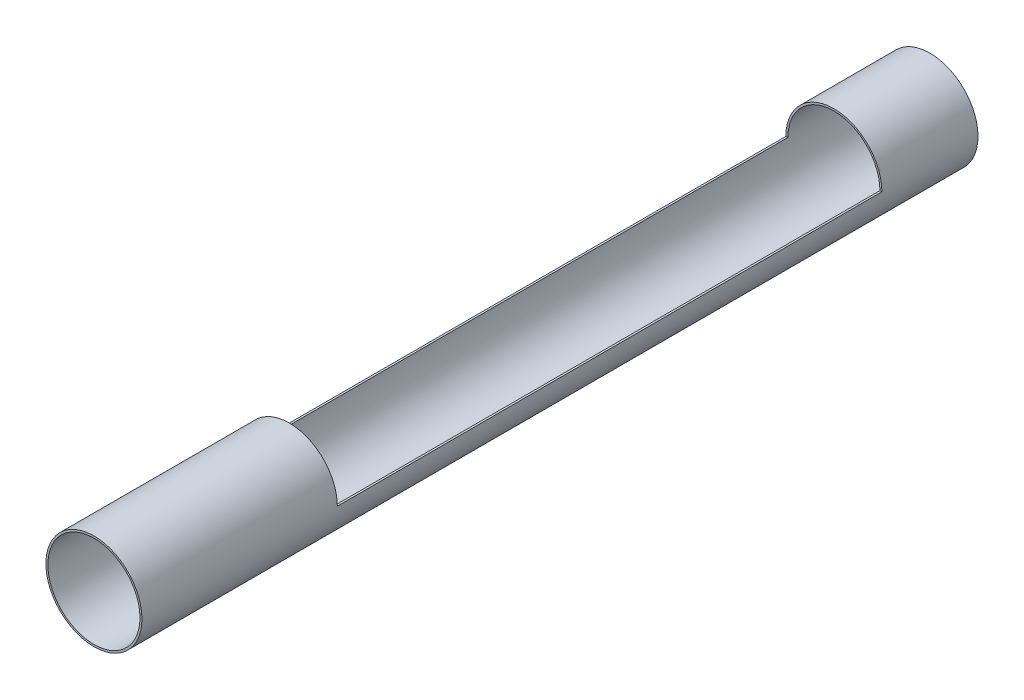
SolidWorks part; units mm, degrees
ref_plane "Front Plane" through (0, 0, 0) normal (0, 0, 1) x (1, 0, 0)
ref_plane "Top Plane" through (0, 0, 0) normal (0, 1, 0) x (1, 0, 0)
ref_plane "Right Plane" through (0, 0, 0) normal (1, 0, 0) x (0, 0, -1)
sketch "Sketch1" plane through (0, 0, 0) normal (0, 0, 1) x (1, 0, 0)
  circle A0 centre (0, 0) radius 36.5125
  circle A1 centre (0, 0) radius 38.0746
  dimension "D1" = 73.025
  dimension "D2" = 76.1492
extrude "Boss-Extrude1" add sketch "Sketch1" along normal blind 76.2
sketch "Sketch2" plane through (0, 0, 76.2) normal (0, 0, 1) x (1, 0, 0)
  line L0 (-38.0746, 0) -> (-36.5125, 0)
  line L1 (38.0746, 0) -> (36.5125, 0)
  arc A0 (-38.0746, 0) -> (38.0746, 0) centre (0, 0) ccw
  arc A1 (-36.5125, 0) -> (36.5125, 0) centre (0, 0) ccw
extrude "Boss-Extrude2" add sketch "Sketch2" along normal blind 431.8
sketch "Sketch3" plane through (0, 0, 508) normal (0, 0, 1) x (1, 0, 0)
  circle A0 centre (0, 0) radius 36.5125
  circle A1 centre (0, 0) radius 38.0746
extrude "Boss-Extrude3" add sketch "Sketch3" along normal blind 154.94
